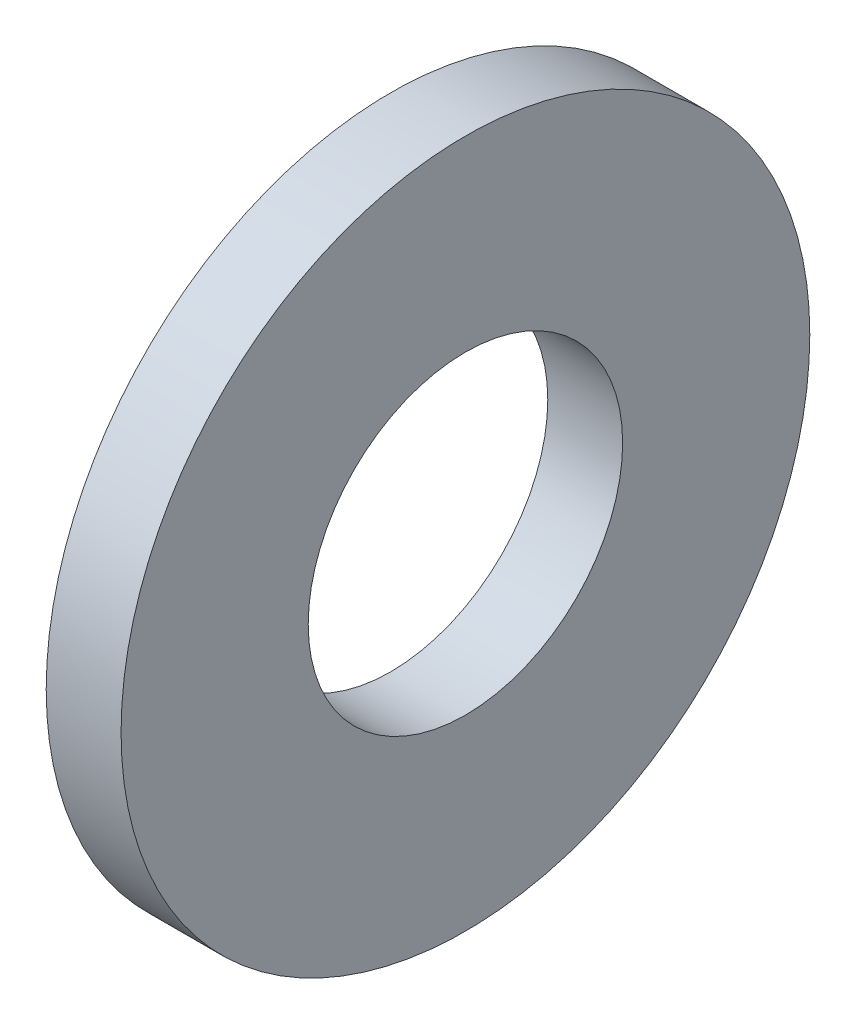
SolidWorks part; units mm, degrees
ref_plane "Plane1" through (0, 0, 0) normal (0, 0, 1) x (1, 0, 0)
ref_plane "Plane2" through (0, 0, 0) normal (0, 1, 0) x (1, 0, 0)
ref_plane "Plane3" through (0, 0, 0) normal (1, 0, 0) x (0, 0, -1)
sketch "Sketch1" plane through (0, 0, 0) normal (1, 0, 0) x (0, 0, -1)
  circle A0 centre (0, 0) radius 5.25
  circle A1 centre (0, 0) radius 11.5
  dimension "Insid_Dia" = 10.5
  dimension "OutsideDia" = 23
extrude "Base-Extrude" add sketch "Sketch1" along normal blind 2.5
